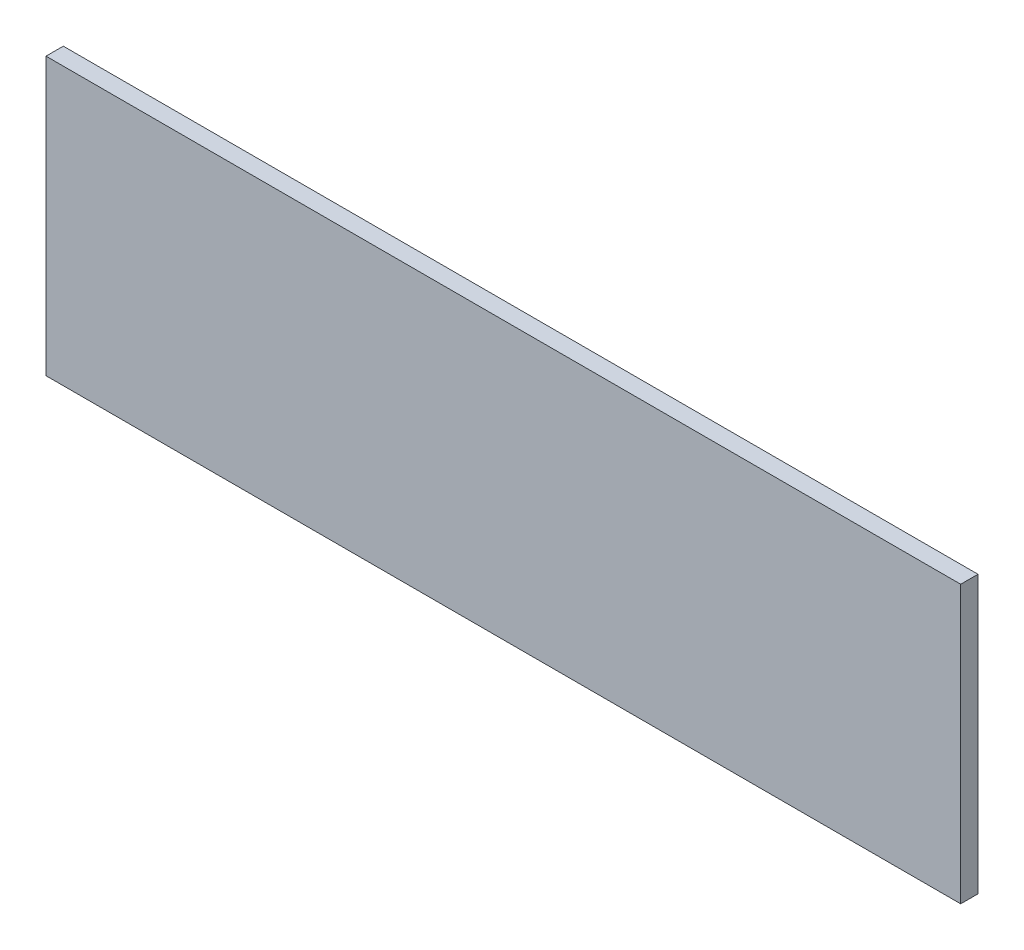
SolidWorks part; units mm, degrees
ref_plane "Front Plane" through (0, 0, 0) normal (0, 0, 1) x (1, 0, 0)
ref_plane "Top Plane" through (0, 0, 0) normal (0, 1, 0) x (1, 0, 0)
ref_plane "Right Plane" through (0, 0, 0) normal (1, 0, 0) x (0, 0, -1)
sketch "Sketch1" plane through (0, 0, 0) normal (0, 0, 1) x (1, 0, 0)
  line L0 (-335.7563, -95.25) -> (335.7562, -95.25)
  line L1 (-335.7562, 298.45) -> (335.7562, 298.45)
  line L2 (-335.7562, 298.45) -> (-335.7562, -298.45)
  line L3 (-335.7562, -298.45) -> (335.7563, -298.45)
  line L4 (335.7562, 298.45) -> (335.7563, -298.45)
  line L5 (-335.7562, 298.45) -> (335.7563, -298.45) construction
  line L6 (-335.7562, -298.45) -> (335.7562, 298.45) construction
  point P0 (0, 0)
  dimension "D1" = 671.5125
  dimension "D2" = 596.9
  dimension "D3" = 203.2
extrude "Boss-Extrude1" add sketch "Sketch1" along normal blind 12.7 contours L4 L0 L2 L3
